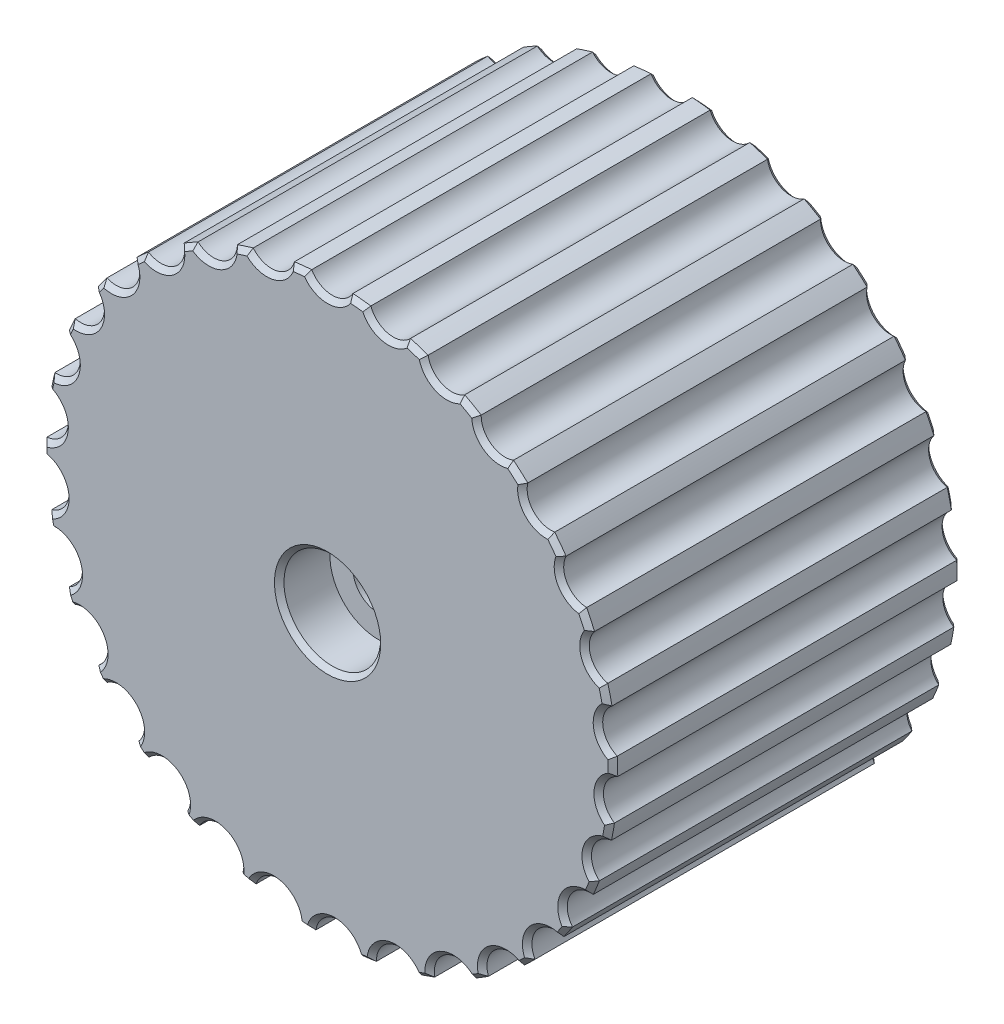
SolidWorks part; units mm, degrees
ref_plane "Ebene vorne" through (0, 0, 0) normal (0, 0, 1) x (1, 0, 0)
ref_plane "Ebene oben" through (0, 0, 0) normal (0, 1, 0) x (1, 0, 0)
ref_plane "Ebene rechts" through (0, 0, 0) normal (1, 0, 0) x (0, 0, -1)
sketch "Skizze1" plane through (0, 0, 0) normal (0, 0, 1) x (1, 0, 0)
  circle A0 centre (0, 0) radius 18
  dimension "D1" = 36
extrude "Grundkörper" add sketch "Skizze1" along normal blind 14
sketch "Skizze3" plane through (0, 0, 0) normal (0, 0, -1) x (-1, 0, 0)
  circle A0 centre (0, 0) radius 11.05
  dimension "D1" = 22.1
extrude "Sitz_Kugellager" cut sketch "Skizze3" against normal blind 7.5
sketch "Skizze4" plane through (0, 0, 0) normal (0, 0, -1) x (-1, 0, 0)
  circle A0 centre (0, 0) radius 15.6
  circle A1 centre (0, 0) radius 18
  circle A2 centre (0, 0) radius 18 construction
  dimension "D1" = 31.2
extrude "Sitz_SchneckenGehäuse" add sketch "Skizze4" along normal blind 8
sketch "Skizze5" plane through (0, 0, 14) normal (0, 0, 1) x (1, 0, 0)
  circle A0 centre (0, 0) radius 1.6
  dimension "D1" = 3.2
extrude "Bohrung M3 Zapfen" cut sketch "Skizze5" against normal through all
sketch "Skizze6" plane through (0, 0, 14) normal (0, 0, 1) x (1, 0, 0)
  circle A0 centre (0, 0) radius 3.05
  dimension "D1" = 6.1
extrude "Senkung M3" cut sketch "Skizze6" against normal blind 3.2
sketch "Skizze7" plane through (0, 0, 14) normal (0, 0, 1) x (1, 0, 0)
  line L0 (0, 18.7) -> (0, 0) construction
  circle A0 centre (0, 18.7) radius 1.5
  circle A2 centre (3.8409, 18.3436) radius 1.5
  circle A3 centre (7.5238, 17.1965) radius 1.5
  circle A4 centre (10.8876, 15.3087) radius 1.5
  circle A5 centre (13.7855, 12.7627) radius 1.5
  circle A6 centre (16.0907, 9.6699) radius 1.5
  circle A7 centre (17.7025, 6.1654) radius 1.5
  circle A8 centre (18.5505, 2.4024) radius 1.5
  circle A9 centre (18.5976, -1.4547) radius 1.5
  circle A10 centre (17.8417, -5.2373) radius 1.5
  circle A11 centre (16.3158, -8.7801) radius 1.5
  circle A12 centre (14.0867, -11.9282) radius 1.5
  circle A13 centre (11.2518, -14.5441) radius 1.5
  circle A14 centre (7.935, -16.5134) radius 1.5
  circle A15 centre (4.2813, -17.75) radius 1.5
  circle A16 centre (0.4502, -18.2) radius 1.5
  circle A17 centre (-3.3907, -17.8436) radius 1.5
  circle A18 centre (-7.0736, -16.6965) radius 1.5
  circle A19 centre (-10.4374, -14.8087) radius 1.5
  circle A20 centre (-13.3353, -12.2627) radius 1.5
  circle A21 centre (-15.6405, -9.1699) radius 1.5
  circle A22 centre (-17.2523, -5.6654) radius 1.5
  circle A23 centre (-18.1003, -1.9024) radius 1.5
  circle A24 centre (-18.1474, 1.9547) radius 1.5
  circle A25 centre (-17.3915, 5.7373) radius 1.5
  circle A26 centre (-15.8656, 9.2801) radius 1.5
  circle A27 centre (-13.6365, 12.4282) radius 1.5
  circle A28 centre (-10.8016, 15.0441) radius 1.5
  circle A29 centre (-7.4848, 17.0134) radius 1.5
  circle A30 centre (-3.8311, 18.25) radius 1.5
  circle A31 centre (0, 0) radius 18 construction
  point P51 (0.2251, 0.25)
  dimension "D1" = 3
  dimension "D3" = 18.7
  dimension "D2" = 30
extrude "Schnitt-Linear austragen3" cut sketch "Skizze7" against normal through all
chamfer "Fase1" distance 0.3 angle 45 122 edges at (3.05, 0, 14) (-1.4624, -17.9405, 14) (-3.1107, -16.37, 14) (-5.2185, -17.2269, 14) (-6.4884, -15.3153, 14) (-8.7445, -15.7332, 14) (-9.5733, -13.5826, 14) (-11.8772, -13.5253, 14) (-12.2312, -11.2474, 14) (-14.4715, -10.704, 14) (-14.3465, -8.4113, 14) (-16.4085, -7.4001, 14) (-15.8272, -5.1975, 14) (-17.6015, -3.7667, 14) (-16.6085, -1.7456, 14) (-18, 0.0282, 14) (-16.656, 1.794, 14) (-17.5918, 3.8115, 14) (-15.967, 5.2674, 14) (-16.4027, 7.413, 14) (-14.5708, 8.5227, 14) (-14.4935, 10.6742, 14) (-12.5279, 11.4178, 14) (-11.9564, 13.4552, 14) (-9.9268, 13.8256, 14) (-8.9092, 15.6405, 14) (-6.8808, 15.6404, 14) (-5.4889, 17.1427, 14) (-3.5229, 16.782, 14) (-1.8452, 17.9052, 14) (0, 17.2, 14) (1.8661, 17.903, 14) (3.5335, 16.8755, 14) (5.4894, 17.1425, 14) (6.9225, 15.8222, 14) (8.8747, 15.6601, 14) (10.0183, 14.0863, 14) (11.8834, 13.5198, 14) (12.6848, 11.7437, 14) (14.3919, 10.8107, 14) (14.805, 8.8973, 14) (16.2963, 7.6441, 14) (16.286, 5.6721, 14) (17.5152, 4.1493, 14) (17.0629, 2.2098, 14) (17.9939, 0.4702, 14) (17.1021, -1.3377, 14) (17.706, -3.2399, 14) (16.4024, -4.8148, 14) (16.6565, -6.8235, 14) (14.9949, -8.0692, 14) (14.8823, -10.1251, 14) (12.942, -10.9589, 14) (12.4522, -12.9978, 14) (10.334, -13.3576, 14) (9.4655, -15.3103, 14) (7.2854, -15.1613, 14) (6.0488, -16.9532, 14) (3.9295, -16.2918, 14) (2.3512, -17.8458, 14) (0.4131, -16.7005, 14) (-15.6, 0, -8) (2.3512, -17.8458, -8) (3.9295, -16.2918, -8) (6.0488, -16.9532, -8) (7.2854, -15.1613, -8) (9.4655, -15.3103, -8) (10.334, -13.3576, -8) (12.4522, -12.9978, -8) (12.942, -10.9589, -8) (14.8823, -10.1251, -8) (14.9949, -8.0692, -8) (16.6565, -6.8235, -8) (16.4024, -4.8148, -8) (17.706, -3.2399, -8) (17.1021, -1.3377, -8) (17.9939, 0.4702, -8) (17.0629, 2.2098, -8) (17.5152, 4.1493, -8) (16.286, 5.6721, -8) (16.2963, 7.6441, -8) (14.805, 8.8973, -8) (14.3919, 10.8107, -8) (12.6848, 11.7437, -8) (11.8834, 13.5198, -8) (10.0183, 14.0863, -8) (8.8747, 15.6601, -8) (6.9225, 15.8222, -8) (5.4894, 17.1425, -8) (3.5335, 16.8755, -8) (1.8661, 17.903, -8) (0, 17.2, -8) (-1.8452, 17.9052, -8) (-3.5229, 16.782, -8) (-5.4889, 17.1427, -8) (-6.8808, 15.6404, -8) (-8.9092, 15.6405, -8) (-9.9268, 13.8256, -8) (-11.9564, 13.4552, -8) (-12.5279, 11.4178, -8) (-14.4935, 10.6742, -8) (-14.5708, 8.5227, -8) (-16.4027, 7.413, -8) (-15.967, 5.2674, -8) (-17.5918, 3.8115, -8) (-16.656, 1.794, -8) (-18, 0.0282, -8) (-16.6085, -1.7456, -8) (-17.6015, -3.7667, -8) (-15.8272, -5.1975, -8) (-16.4085, -7.4001, -8) (-14.3465, -8.4113, -8) (-14.4715, -10.704, -8) (-12.2312, -11.2474, -8) (-11.8772, -13.5253, -8) (-9.5733, -13.5826, -8) (-8.7445, -15.7332, -8) (-6.4884, -15.3153, -8) (-5.2185, -17.2269, -8) (-3.1107, -16.37, -8) (-1.4624, -17.9405, -8) (0.4131, -16.7005, -8)
sketch "Skizze8" plane through (0, 0, 0) normal (0, 0, -1) x (-1, 0, 0)
  line L0 (0, 0) -> (0, 11.05) construction
  line L1 (4.2287, 10.2089) -> (4.42, 10.6708)
  line L2 (-4.2287, 10.2089) -> (-4.42, 10.6708)
  line L3 (6.7268, 8.7666) -> (7.0312, 9.1632)
  line L4 (10.9555, 1.4423) -> (11.4512, 1.5076)
  line L5 (10.9555, -1.4423) -> (11.4512, -1.5076)
  line L6 (6.7268, -8.7666) -> (7.0312, -9.1632)
  line L7 (4.2287, -10.2089) -> (4.42, -10.6708)
  line L8 (-4.2287, -10.2089) -> (-4.42, -10.6708)
  line L9 (-6.7268, -8.7666) -> (-7.0312, -9.1632)
  line L10 (-10.9555, -1.4423) -> (-11.4512, -1.5076)
  line L11 (-10.9555, 1.4423) -> (-11.4512, 1.5076)
  line L12 (-6.7268, 8.7666) -> (-7.0312, 9.1632)
  circle A0 centre (0, 0) radius 11.05 construction
  arc A1 (-4.42, -10.6708) -> (4.42, -10.6708) centre (0, 0) ccw
  arc A3 (-4.2287, 10.2089) -> (-6.7268, 8.7666) centre (0, 0) ccw
  arc A4 (-10.9555, 1.4423) -> (-10.9555, -1.4423) centre (0, 0) ccw
  arc A5 (-6.7268, -8.7666) -> (-4.2287, -10.2089) centre (0, 0) ccw
  arc A6 (4.2287, -10.2089) -> (6.7268, -8.7666) centre (0, 0) ccw
  arc A7 (-11.4512, -1.5076) -> (-7.0312, -9.1632) centre (0, 0) ccw
  arc A8 (7.0312, -9.1632) -> (11.4512, -1.5076) centre (0, 0) ccw
  arc A9 (10.9555, -1.4423) -> (10.9555, 1.4423) centre (0, 0) ccw
  arc A10 (11.4512, 1.5076) -> (7.0312, 9.1632) centre (0, 0) ccw
  arc A11 (6.7268, 8.7666) -> (4.2287, 10.2089) centre (0, 0) ccw
  arc A12 (4.42, 10.6708) -> (-4.42, 10.6708) centre (0, 0) ccw
  arc A13 (-7.0312, 9.1632) -> (-11.4512, 1.5076) centre (0, 0) ccw
  point P23 (0, 0)
  dimension "D1" = 0.5
  dimension "D2" = 45
  dimension "D3" = 6
extrude "FreischnittKugellager" cut sketch "Skizze8" against normal up to surface (7.5 mm away) up to face at (-1.6, 0, 7.5)
chamfer "Fase2" distance 0.4 angle 45 6 edges at (11.05, 0, 0) (5.525, -9.5696, 0) (-5.525, -9.5696, 0) (-11.05, 0, 0) (-5.525, 9.5696, 0) (5.525, 9.5696, 0)
